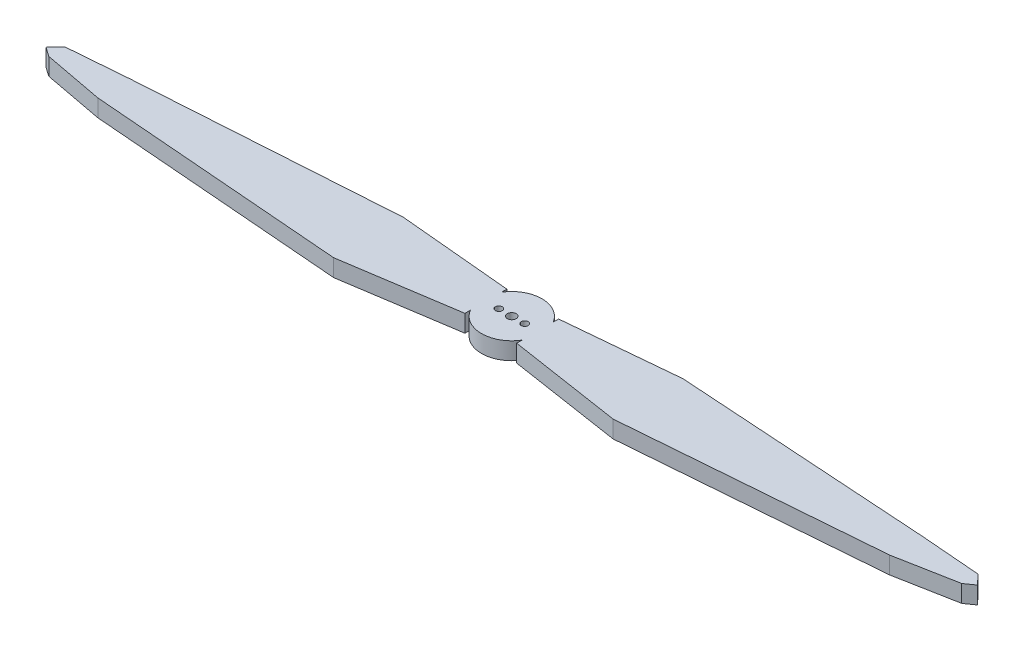
SolidWorks part; units mm, degrees
ref_plane "Front Plane" through (0, 0, 0) normal (0, 0, 1) x (1, 0, 0)
ref_plane "Top Plane" through (0, 0, 0) normal (0, 1, 0) x (1, 0, 0)
ref_plane "Right Plane" through (0, 0, 0) normal (1, 0, 0) x (0, 0, -1)
sketch "Sketch1" plane through (0, 0, 0) normal (0, 1, 0) x (1, 0, 0)
  line L0 (12, -9.7155) -> (64.77, -17.8117)
  line L1 (64.77, -17.8117) -> (183.515, -8.3122)
  line L2 (183.515, -8.3122) -> (211.582, -3.0226)
  line L3 (211.582, -3.0226) -> (215.9, 0)
  line L4 (215.9, 0) -> (211.582, 4.5339)
  line L5 (211.582, 4.5339) -> (183.515, 6.8009)
  line L6 (183.515, 6.8009) -> (64.77, 14.5732)
  line L7 (64.77, 14.5732) -> (12, 9.7155)
  line L8 (12, 9.7155) -> (12, -9.7155)
  line L9 (-12, -9.7155) -> (-64.77, -17.8117)
  line L10 (-64.77, -17.8117) -> (-183.515, -8.3122)
  line L11 (-183.515, -8.3122) -> (-211.582, -3.0226)
  line L12 (-211.582, -3.0226) -> (-215.9, 0)
  line L13 (-215.9, 0) -> (-211.582, 4.5339)
  line L14 (-211.582, 4.5339) -> (-183.515, 6.8009)
  line L15 (-183.515, 6.8009) -> (-64.77, 14.5732)
  line L16 (-64.77, 14.5732) -> (-12, 9.7155)
  line L17 (-12, 9.7155) -> (-12, -9.7155)
extrude "Boss-Extrude1" add sketch "Sketch1" along normal blind 8
sketch "Sketch2" plane through (0, 0, 0) normal (0, 1, 0) x (1, 0, 0)
  circle A0 centre (0, 0) radius 14
extrude "Boss-Extrude2" add sketch "Sketch2" along normal blind 8
sketch "Sketch3" plane through (0, 0, 0) normal (0, 1, 0) x (1, 0, 0)
  circle A0 centre (0, 0) radius 2.05
  circle A1 centre (6, 0) radius 1.6
  circle A2 centre (-6, 0) radius 1.6
extrude "Cut-Extrude1" cut sketch "Sketch3" against normal through all and the other way through all
